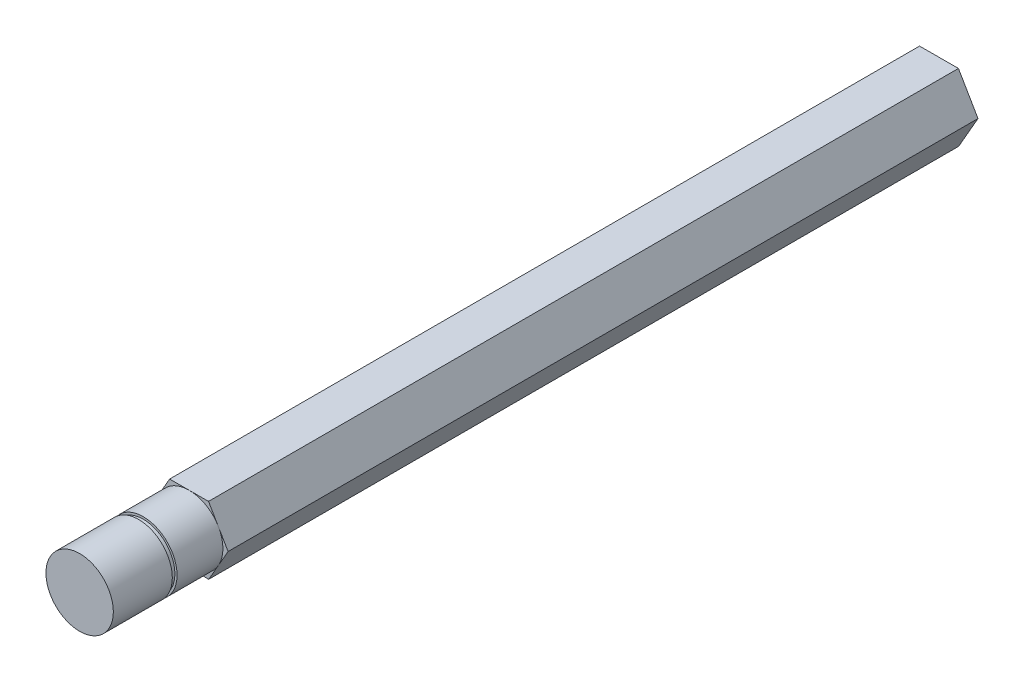
SolidWorks part; units mm, degrees
material "6061 Alloy"
ref_plane "Front Plane" through (0, 0, 0) normal (0, 0, 1) x (1, 0, 0)
ref_plane "Top Plane" through (0, 0, 0) normal (0, 1, 0) x (1, 0, 0)
ref_plane "Right Plane" through (0, 0, 0) normal (1, 0, 0) x (0, 0, -1)
sketch "Sketch1" plane through (0, 0, 0) normal (0, 0, 1) x (1, 0, 0)
  line L1 (3.6846, -6.3393) -> (7.3323, 0.0213)
  line L2 (7.3323, 0.0213) -> (3.6477, 6.3606)
  line L3 (3.6477, 6.3606) -> (-3.6846, 6.3393)
  line L4 (-3.6846, 6.3393) -> (-7.3323, -0.0213)
  line L5 (-7.3323, -0.0213) -> (-3.6477, -6.3606)
  line L6 (-3.6477, -6.3606) -> (3.6846, -6.3393)
  circle A0 centre (0, 0) radius 6.35 construction
  dimension ".5" = 12.7
extrude "Boss-Extrude1" add sketch "Sketch1" along normal mid plane 152.4
sketch "Sketch2" plane through (0, 0, 76.2) normal (0, 0, 1) x (1, 0, 0)
  circle A0 centre (0, 0) radius 6.35
  circle A1 centre (0, 0) radius 7.3323
  dimension ".5" = 12.7
extrude "Cut-Extrude1" cut sketch "Sketch2" against normal blind 11.1125
sketch "Sketch3" plane through (0, 0, 76.2) normal (0, 0, 1) x (1, 0, 0)
  circle A0 centre (0, 0) radius 6.35
  dimension "D1" = 12.7
extrude "Boss-Extrude2" add sketch "Sketch3" along normal blind 9.525
ref_plane "Plane1" through (0, 0, 74.6125) normal (0, 0, 1) x (1, 0, 0)
sketch "Sketch4" plane through (0, 0, 74.6125) normal (0, 0, 1) x (1, 0, 0)
  circle A0 centre (0, 0) radius 5.9436
  circle A1 centre (0, 0) radius 7.3323
  dimension ".468" = 11.8872
extrude "Cut-Extrude2" cut sketch "Sketch4" against normal blind 0.889
